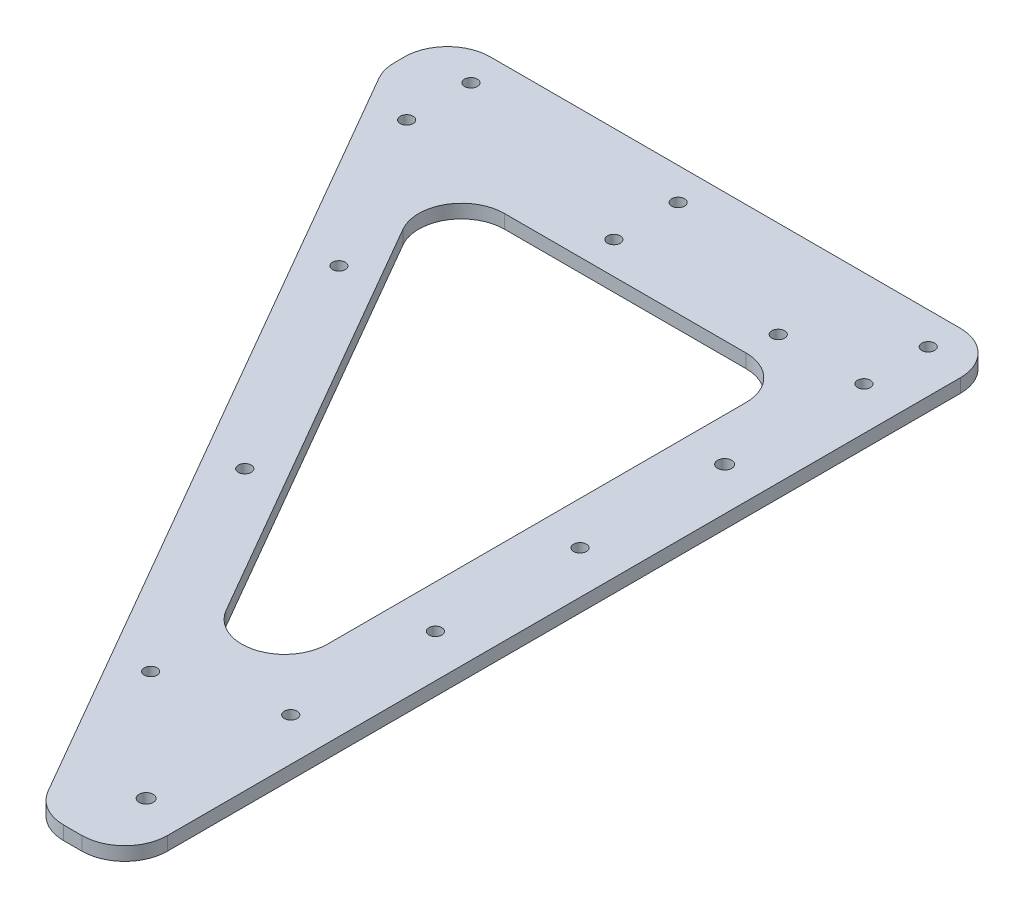
SolidWorks part; units mm, degrees
ref_plane "Front" through (0, 0, 0) normal (0, 0, 1) x (1, 0, 0)
ref_plane "Top" through (0, 0, 0) normal (0, 1, 0) x (1, 0, 0)
ref_plane "Right" through (0, 0, 0) normal (1, 0, 0) x (0, 0, -1)
sketch "Sketch1" plane through (0, 0, 0) normal (0, 1, 0) x (1, 0, 0)
  line L0 (-20, -190) -> (-129.6966, 0)
  line L1 (0, 0) -> (-20, 0)
  line L2 (0, 0) -> (0, -190)
  line L3 (0, -190) -> (-20, -190)
  line L4 (-20, 0) -> (-20, -190)
  line L5 (-129.6966, 0) -> (-20, 0)
  line L6 (-10, -190) -> (-10, -175)
  line L7 (-10, -175) -> (-10, -40)
  line L8 (-13.5048, -186.25) -> (-116.7062, -7.5)
  line L9 (-116.7062, -7.5) -> (-20, -7.5)
  line L10 (-7.0096, -182.5) -> (-103.7158, -15)
  line L11 (-103.7158, -15) -> (-20, -15)
  circle A0 centre (-10, -175) radius 1.65
  circle A1 centre (-10, -40) radius 1.65
  circle A2 centre (-116.7062, -7.5) radius 1.5
  circle A3 centre (-68.3531, -7.5) radius 1.5
  circle A5 centre (-10, -107.5) radius 1500
  circle A6 centre (-10, -7.5) radius 1.5
  circle A7 centre (-10, -107.5) radius 1.5
  circle A8 centre (-10, -141.25) radius 1.5
  circle A9 centre (-10, -73.75) radius 1.5
  circle A10 centre (-65.1055, -96.875) radius 1.5
  circle A11 centre (-95.1055, -44.9135) radius 1.5
  circle A12 centre (-35.1055, -148.8365) radius 1.5
  circle A13 centre (-30, -7.5) radius 1.5
  point P37 (0, 0)
  dimension "D6" = 7.5
  dimension "D7" = 33.75
  dimension "D10" = 60
  dimension "D1" = 20
  dimension "D2" = 190
  dimension "D3" = 109.6966
  dimension "D4" = 15
  dimension "D5" = 135
  dimension "D8" = 33.75
  dimension "D11" = 60
  dimension "D12" = 10
  dimension "D9" = 15
extrude "Boss-Extrude1" add sketch "Sketch1" along normal blind 3.175
sketch "Sketch2" plane through (0, 0, 0) normal (0, -1, 0) x (1, 0, 0)
  line L0 (-129.6966, 0) -> (0, 0)
  line L1 (-129.6966, 0) -> (-129.6966, -15)
  line L2 (0, 0) -> (0, -15)
  line L3 (-129.6966, -15) -> (0, -15)
  line L4 (-116.7062, 7.5) -> (-116.7062, -7.5)
  line L5 (-68.3531, 7.5) -> (-68.3531, -7.5)
  line L6 (-10, 7.5) -> (-10, -7.5)
  circle A0 centre (-116.7062, -7.5) radius 1.5
  circle A1 centre (-68.3531, -7.5) radius 1.5
  circle A2 centre (-10, -7.5) radius 1.5
  dimension "D1" = 15
  dimension "D2" = 15
  dimension "D3" = 15
  dimension "D4" = 15
extrude "Boss-Extrude2" add sketch "Sketch2" against normal blind 3.175
fillet "Fillet1" radius 10 8 edges at (-20, 1.5875, 160) (-20, 1.5875, 15) (-103.7158, 1.5875, 15) (-129.6966, 1.5875, -15) (0, 1.5875, -15) (0, 1.5875, 190) (-20, 1.5875, 190) (-129.6966, 1.5875, 0)
